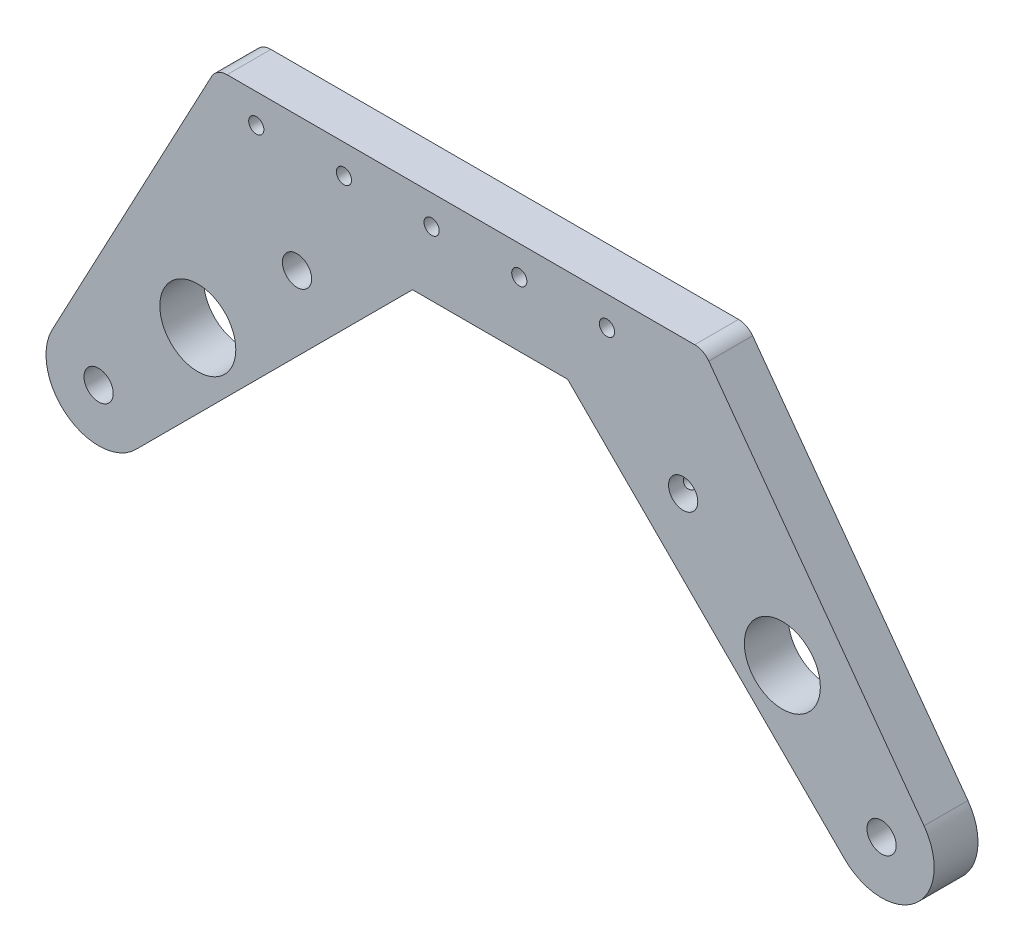
SolidWorks part; units mm, degrees
ref_plane "前基準面" through (0, 0, 0) normal (0, 0, 1) x (1, 0, 0)
ref_plane "上基準面" through (0, 0, 0) normal (0, 1, 0) x (1, 0, 0)
ref_plane "右基準面" through (0, 0, 0) normal (1, 0, 0) x (0, 0, -1)
sketch "草圖2" plane through (0, 0, 0) normal (0, 0, 1) x (1, 0, 0)
  line L3 (0, 0) -> (40, 0) construction
  line L4 (40, 0) -> (40, 40) construction
  line L7 (0, 0) -> (40, 40) construction
  line L8 (100, 0) -> (40, 0) construction
  line L18 (40, 40) -> (40, 35) construction
  line L19 (40, 35) -> (25, 35) construction
  line L22 (40, 35) -> (55, 35) construction
  line L23 (55, 35) -> (70, 35) construction
  line L24 (25, 35) -> (10, 35) construction
  line L27 (60, 40) -> (100, 0) construction
  line L28 (40, 40) -> (60, 40) construction
  line L29 (40, 40) -> (5, 40)
  line L30 (40, 40) -> (85, 40)
  line L31 (87.423, 38.7689) -> (124.2397, -11.664)
  line L35 (36.7279, 24) -> (-10.6066, -23.3345)
  line L37 (2.3526, 38.4112) -> (-24.9126, -12.7369)
  line L38 (110.6066, -23.3345) -> (63.2721, 24)
  line L40 (36.7279, 24) -> (63.2721, 24)
  line L44 (100, 0) -> (122.0971, -22.0971) construction
  line L46 (0, 0) -> (-22.0971, -22.0971) construction
  line L47 (100, 0) -> (83.0294, 16.9706) construction
  line L48 (0, 0) -> (16.9706, 16.9706) construction
  line L50 (0, 0) -> (-16.9706, -16.9706) construction
  line L52 (100, 0) -> (116.9706, -16.9706) construction
  circle A10 centre (0, 0) radius 6.5
  circle A15 centre (100, 0) radius 6.5
  circle A18 centre (25, 35) radius 1.3
  circle A19 centre (70, 35) radius 1.3
  circle A20 centre (40, 35) radius 1.3
  circle A21 centre (55, 35) radius 1.3
  circle A24 centre (10, 35) radius 1.3
  arc A27 (2.3526, 38.4112) -> (5, 40) centre (5, 37) cw
  arc A28 (85, 40) -> (87.423, 38.7689) centre (85, 37) cw
  circle A31 centre (16.9706, 16.9706) radius 2.5
  circle A32 centre (83.0294, 16.9706) radius 2.5
  circle A33 centre (-16.9706, -16.9706) radius 2.5
  circle A34 centre (116.9706, -16.9706) radius 2.5
  arc A35 (-24.9126, -12.7369) -> (-10.6066, -23.3345) centre (-16.9706, -16.9706) ccw
  arc A36 (110.6066, -23.3345) -> (124.2397, -11.664) centre (116.9706, -16.9706) ccw
  point P9 (40, 8)
  point P31 (40, 16)
  point P35 (40, 24)
  point P36 (40, 32)
  dimension "D2" = 60
  dimension "D4" = 40
  dimension "D5" = 45
  dimension "D3" = 24
  dimension "D6" = 45
  dimension "D7" = 2.6
  dimension "D8" = 3
  dimension "D10" = 31.25
  dimension "D9" = 13
  dimension "D11" = 5
  dimension "D13" = 3
  dimension "D16" = 24
  dimension "D17" = 5
  dimension "D19" = 18
  dimension "D12" = 15
  dimension "D14" = 45
  dimension "D15" = 35
  dimension "D18" = 24
extrude "填料-伸長1" add sketch "草圖2" along normal blind 7.5 contours L29 A27 L37 A35 L35 L40 L38 A36 L31 A28 L30 | A10 | A15 | A19 | A18 | A21 | A20 | A24 | A31 | A32 | A34 | A33
ref_plane "平面1" through (6.364, -6.364, 0) normal (0.7071, -0.7071, 0) x (-0.7071, -0.7071, 0)
sketch "草圖4" plane through (6.364, -6.364, 0) normal (0.7071, -0.7071, 0) x (-0.7071, -0.7071, 0)
  line L1 (24, -7.5) -> (24, -3.75) construction
  line L2 (24, -7.5) -> (24, 0) construction
  line L3 (24, -3.75) -> (-5, -3.75) construction
  line L7 (-5, -3.75) -> (-15, -3.75) construction
  line L8 (-15, -3.75) -> (-25, -3.75) construction
  line L9 (-25, -3.75) -> (-35, -3.75) construction
  circle A1 centre (-25, -3.75) radius 1.3
  circle A2 centre (-35, -3.75) radius 1.3
  dimension "D2" = 29
  dimension "D3" = 2.6
  dimension "D1" = 10
ref_plane "平面2" through (43.636, 43.636, 0) normal (-0.7071, -0.7071, 0) x (-0.7071, 0.7071, 0)
sketch "草圖10" plane through (43.636, 43.636, 0) normal (-0.7071, -0.7071, 0) x (-0.7071, 0.7071, 0)
  line L3 (-55.7107, -3.75) -> (-45.7107, -3.75) construction
  line L4 (-45.7107, -3.75) -> (-35.7107, -3.75) construction
  line L6 (-94.7107, -7.5) -> (-94.7107, -3.75) construction
  line L7 (-65.7107, -3.75) -> (-55.7107, -3.75) construction
  line L8 (-94.7107, -7.5) -> (-94.7107, 0) construction
  line L9 (-94.7107, -3.75) -> (-65.7107, -3.75) construction
  circle A1 centre (-45.7107, -3.75) radius 1.3
  circle A2 centre (-35.7107, -3.75) radius 1.3
  dimension "D2" = 2.6
  dimension "D1" = 10
  dimension "D3" = 29
extrude "除料-伸長2" cut sketch "草圖10" against normal blind 7.5
ref_plane "平面3" through (0, 0, 0) normal (0, 0, 1) x (1, 0, 0)
extrude "除料-伸長4" cut sketch "草圖4" against normal blind 7.5
chamfer "導角2" distance 0.2 2 edges at (76.8776, 10.3945, 3.75) (69.8065, 17.4655, 3.75)
chamfer "導角3" distance 0.2 angle 45 2 edges at (24.9609, 12.2329, 3.75) (32.0319, 19.304, 3.75)
chamfer "導角4" distance 0.5 4 edges at (-14.4706, -16.9706, 0) (19.4706, 16.9706, 0) (119.4706, -16.9706, 0) (85.5294, 16.9706, 0)
